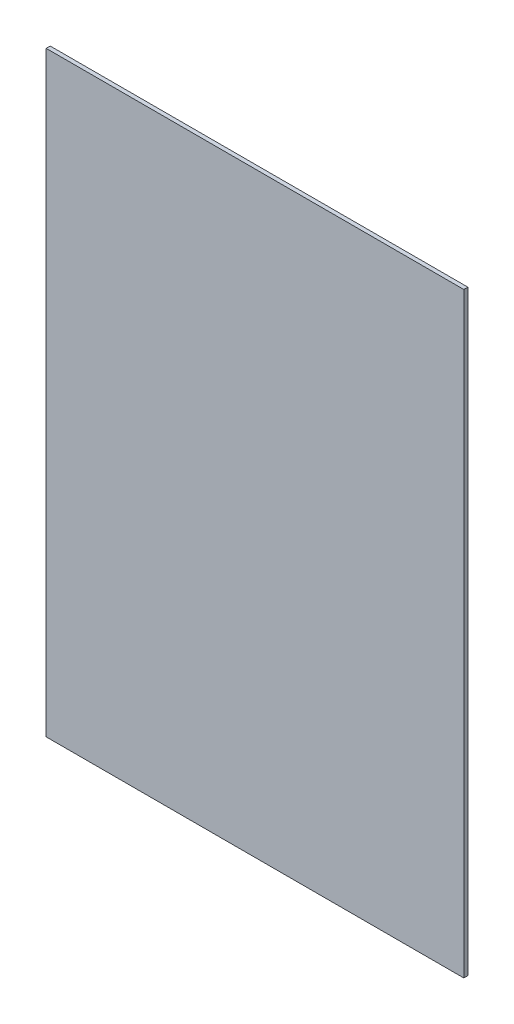
SolidWorks part; units mm, degrees
ref_plane "Front Plane" through (0, 0, 0) normal (0, 0, 1) x (1, 0, 0)
ref_plane "Top Plane" through (0, 0, 0) normal (0, 1, 0) x (1, 0, 0)
ref_plane "Right Plane" through (0, 0, 0) normal (1, 0, 0) x (0, 0, -1)
sketch "Sketch1" plane through (0, 0, 0) normal (0, 0, 1) x (1, 0, 0)
  line L0 (11.2291, -295) -> (321.2291, -295) construction
  line L1 (8.2291, 0) -> (214.8516, 0)
  line L2 (8.2291, 0) -> (8.2291, -295)
  line L3 (8.2291, -295) -> (214.8516, -295)
  line L4 (214.8516, 0) -> (214.8516, -295)
extrude "Boss-Extrude1" add sketch "Sketch1" along normal blind 2
